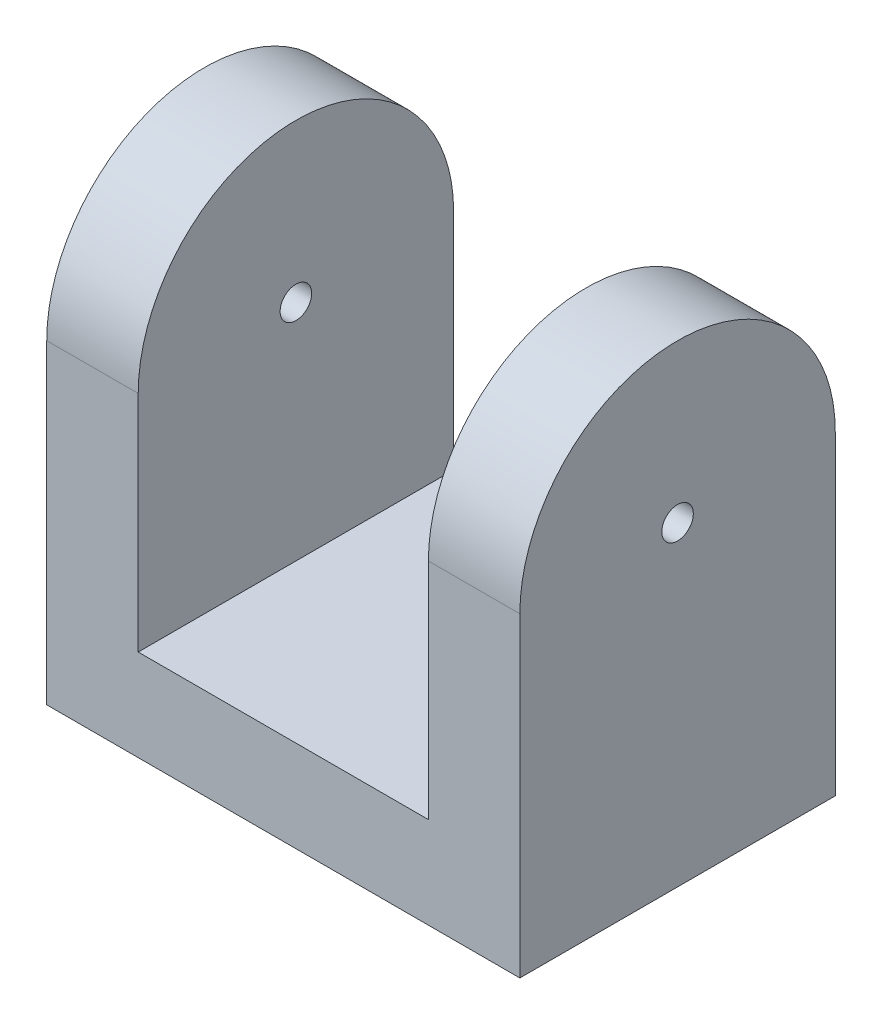
SolidWorks part; units mm, degrees
ref_plane "Ebene vorne" through (0, 0, 0) normal (0, 0, 1) x (1, 0, 0)
ref_plane "Ebene oben" through (0, 0, 0) normal (0, 1, 0) x (1, 0, 0)
ref_plane "Ebene rechts" through (0, 0, 0) normal (1, 0, 0) x (0, 0, -1)
sketch "Skizze1" plane through (0, 0, 0) normal (1, 0, 0) x (0, 0, -1)
  line L0 (-50, 0) -> (-50, -100)
  line L1 (-50, -100) -> (50, -100)
  line L2 (50, -100) -> (50, 0)
  circle A0 centre (0, 0) radius 50
  circle A1 centre (0, 0) radius 5
  dimension "D1" = 100
  dimension "D2" = 100
extrude "Aufsatz-Linear austragen1" add sketch "Skizze1" along normal blind 150 contours A0 A1 | A0 L0 L1 L2
sketch "Skizze2" plane through (0, 0, 50) normal (0, 0, 1) x (1, 0, 0)
  line L0 (0, 50) -> (29, 50)
  line L1 (150, 50) -> (0, 50) construction
  line L2 (150, 50) -> (121, 50)
  line L3 (29, 50) -> (121, 50)
  line L4 (29, 50) -> (29, -71)
  line L5 (29, -71) -> (121, -71)
  line L6 (121, 50) -> (121, -71)
  line L7 (150, -100) -> (0, -100) construction
  line M10 (150, 0) -> (0, 0)
  dimension "D1" = 29
  dimension "D2" = 29
  dimension "D3" = 29
extrude "Schnitt-Linear austragen1" cut sketch "Skizze2" against normal through all contours L6 L3 L4 M10 | L6 L4 L5 M10
